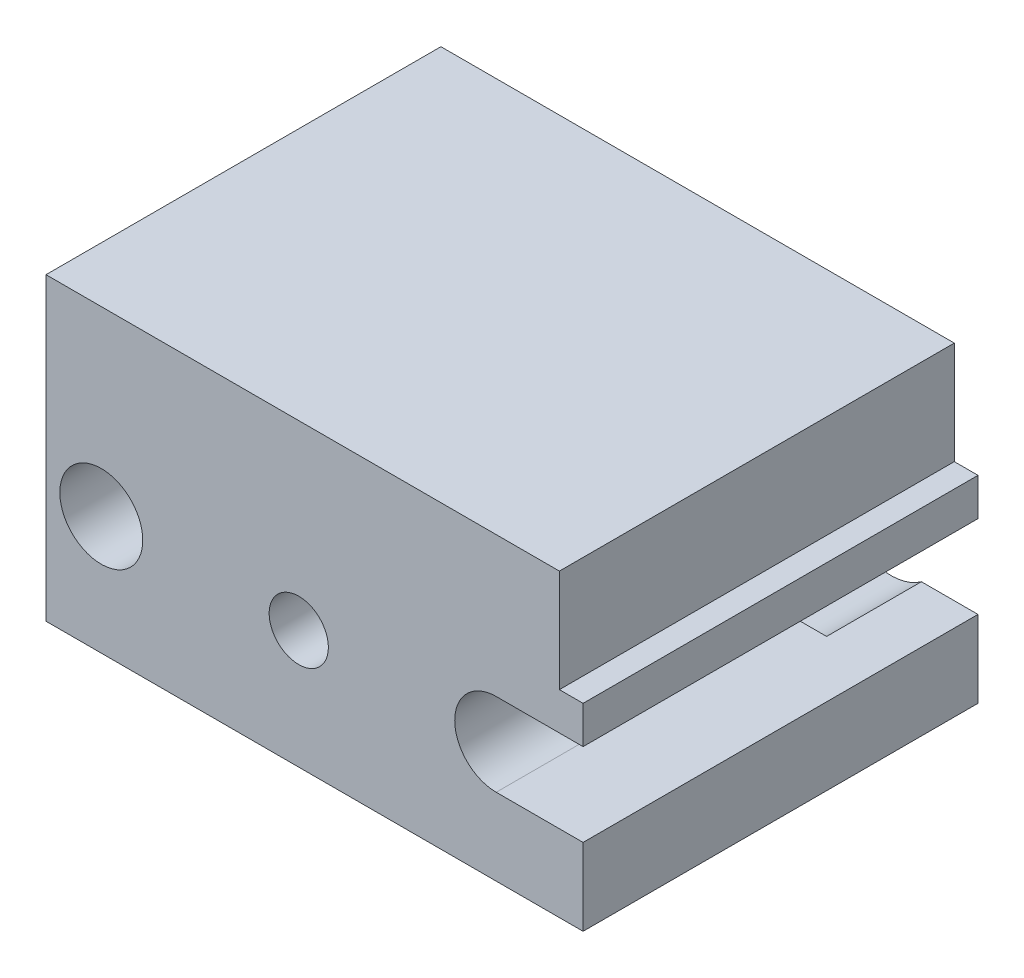
SolidWorks part; units mm, degrees
material "Polyetheretherketone (PEEK)"
ref_plane "Front Plane" through (0, 0, 0) normal (0, 0, 1) x (1, 0, 0)
ref_plane "Top Plane" through (0, 0, 0) normal (0, 1, 0) x (1, 0, 0)
ref_plane "Right Plane" through (0, 0, 0) normal (1, 0, 0) x (0, 0, -1)
ref_plane "Plane1" through (0, 4, 0) normal (0, 1, 0) x (-1, 0, 0)
sketch "Sketch1" plane through (0, 4, 0) normal (0, 1, 0) x (-1, 0, 0)
  line L0 (0, 0) -> (0, 5)
  line L1 (0, 5) -> (-6.8, 5)
  line L2 (-6.8, 5) -> (-6.8, 0)
  line L3 (-6.8, 0) -> (0, 0)
  dimension "D1" = 5
  dimension "D2" = 6.8
extrude "Boss-Extrude1" add sketch "Sketch1" against normal blind 3.8
sketch "Sketch3" plane through (0, 0, 5) normal (0, 0, 1) x (1, 0, 0)
  line L0 (1.8, 0.2) -> (4.6, 0.2)
  line L1 (4.6, 0.2) -> (4.6, 3.1)
  line L2 (4.6, 3.1) -> (1.8, 3.1)
  line L3 (1.8, 3.1) -> (1.8, 0.2)
  line L4 (0, 0.2) -> (6.8, 0.2) construction
  dimension "D1" = 2.8
  dimension "D2" = 2.9
sketch "Sketch4" plane through (6.8, 0, 0) normal (1, 0, 0) x (0, 0, -1)
  line L0 (-2.85, 0.2) -> (-0.95, 0.2)
  line L1 (-0.95, 0.2) -> (-0.95, 0.4)
  line L2 (-0.95, 0.4) -> (-2.85, 0.4)
  line L3 (-2.85, 0.4) -> (-2.85, 0.2)
  line L4 (-5, 0.2) -> (0, 0.2) construction
  dimension "D1" = 0.2
hole_wizard "Hole1" positions "Sketch7" profile "Sketch6" legacy end condition through all
sketch "Sketch7" plane through (0, 0, 0) normal (0, 0, -1) x (-1, 0, 0)
  point P0 (-5.7, 1.7)
  point P1 (-0.7, 1.7)
  dimension "D1" = 5
  dimension "D2" = 1.5
  dimension "D3" = 0.7
  dimension "D4" = 5.7
sketch "Sketch6" plane through (5.7, 1.7, 0) normal (1, 0, 0) x (0, 1, 0)
  line L0 (0, 0) -> (0, 5)
  line L1 (0, 5) -> (0.525, 5)
  line L2 (0.525, 5) -> (0.525, 1.2)
  line L3 (0.525, 1.2) -> (0.65, 1.2)
  line L4 (0.65, 1.2) -> (0.65, 0)
  line L5 (0.65, 0) -> (0, 0)
  line L6 (0, 110) -> (0, -10) construction
  dimension "Diameter" = 1.05
  dimension "Depth" = 5
  dimension "C-Bore Diameter" = 1.3
  dimension "C-Bore Depth" = 1.2
sketch "Sketch17" plane through (0, 0, 5) normal (0, 0, 1) x (1, 0, 0)
  line L0 (6.8, 4) -> (6.8, 0.2) construction
  line L2 (0, 0.2) -> (6.8, 0.2) construction
  line L4 (5.7, 2.225) -> (6.8, 2.225)
  line L5 (5.7, 2.225) -> (5.7, 1.175)
  line L6 (5.7, 1.175) -> (6.8, 1.175)
  line L7 (6.8, 2.225) -> (6.8, 1.175)
  circle A0 centre (5.7, 1.7) radius 0.525
  circle M1 centre (5.7, 1.7) radius 0.525
  line M12 (6.8, 0.2) -> (6.8, 4)
  dimension "D1" = 1.05
  dimension "D2" = 1.1
  dimension "D3" = 1.5
extrude "Cut-Extrude8" cut sketch "Sketch17" against normal through all contours L6 L4 M1 M12 | L5 M1 | L5 M1
sketch "Sketch18" plane through (6.8, 0, 0) normal (1, 0, 0) x (0, 0, -1)
  line L0 (-3.7113, 4) -> (-4, 3.5)
  line L1 (-5, 4) -> (-5, 2.225) construction
  line L2 (-5, 4) -> (0, 4) construction
  line L3 (-4, 3.5) -> (-1, 3.5)
  line L4 (-1, 3.5) -> (-1.2887, 4)
  line L8 (-1.2887, 4) -> (-3.7113, 4)
  dimension "D1" = 3
  dimension "D2" = 60
  dimension "D3" = 60
  dimension "D4" = 1
  dimension "D5" = 0.5
sketch "Sketch20" plane through (6.8, 0, 0) normal (1, 0, 0) x (0, 0, -1)
  line L0 (0, 2.225) -> (0, 4) construction
  line L1 (-5, 4) -> (0, 4)
  line L2 (-5, 4) -> (-5, 2.7)
  line L3 (-5, 2.7) -> (0, 2.7)
  line L4 (0, 4) -> (0, 2.7)
  dimension "D1" = 1.3
extrude "Cut-Extrude11" cut sketch "Sketch20" against normal blind 0.3
sketch "Sketch22" plane through (0, 0, 0) normal (0, 0, -1) x (-1, 0, 0)
  line L0 (-6.8, 0.2) -> (0, 0.2) construction
  line L1 (-6.8, 0.2) -> (-6.8, 1.175) construction
  line L3 (-5.6, 2.35) -> (-6.8, 2.35)
  line L4 (-5.6, 2.35) -> (-5.6, 1.05)
  line L5 (-5.6, 1.05) -> (-6.8, 1.05)
  line L6 (-6.8, 2.35) -> (-6.8, 1.05)
  circle A0 centre (-5.6, 1.7) radius 0.65
  line M2 (-6.8, 2.7) -> (-6.8, 2.225)
  line M3 (-6.8, 2.225) -> (-6.0832, 2.225)
  arc M4 (-6.0832, 2.225) -> (-6.0832, 1.175) centre (-5.7, 1.7) cw
  line M5 (-6.0832, 1.175) -> (-6.8, 1.175)
  line M6 (-6.8, 1.175) -> (-6.8, 0.2)
  dimension "D1" = 1.3
  dimension "D2" = 1.5
  dimension "D3" = 1.2
extrude "Cut-Extrude12" [suppressed] cut sketch "Sketch22" against normal blind 1.2 contours A0 L6 M4 M3 M5 | A0 L4 M4 | L4 M4 | L4 A0 M4 | L3 M4 M2 M3 | L5 M4 M5 M6 | A0 L4 M4 | A0 L5 M4 | A0 L3 M4 | L4 A0 M4
hole_wizard "M1.0x0.25 Tapped Hole1" positions "Sketch32" profile "Sketch34" tap size "M1.0x0.25" standard "ANSI Metric" end condition up to next
sketch "Sketch32" plane through (0, 0, 0) normal (0, 0, -1) x (-1, 0, 0)
  line L0 (-5.7, 1.7) -> (-0.7, 1.7) construction
  circle A0 centre (-0.7, 1.7) radius 0.65 construction
  circle A1 centre (-0.7, 1.7) radius 0.65
  arc A2 (-6.0832, 1.175) -> (-6.0832, 2.225) centre (-5.7, 1.7) ccw construction
  arc A3 (-6.0832, 1.175) -> (-6.0832, 2.225) centre (-5.7, 1.7) ccw
  point P20 (-3.2, 1.7)
  point P23 (0, 0)
  point P24 (0, 0)
cosmetic thread "Hole Thread4" parameters "D2"=25.4
sketch "Sketch34" plane through (3.2, 1.7, 0) normal (1, 0, 0) x (0, 1, 0)
  line L0 (0, 0) -> (0, 5)
  line L1 (0, 5) -> (0.375, 5)
  line L2 (0.375, 5) -> (0.375, 0)
  line L5 (0.375, 0) -> (0, 0)
  line L11 (0, -6.35) -> (0, 107.95) construction
  dimension "Thru Tap Drill Dia." = 0.75
  dimension "Thru Tap Drill Depth" = 5
